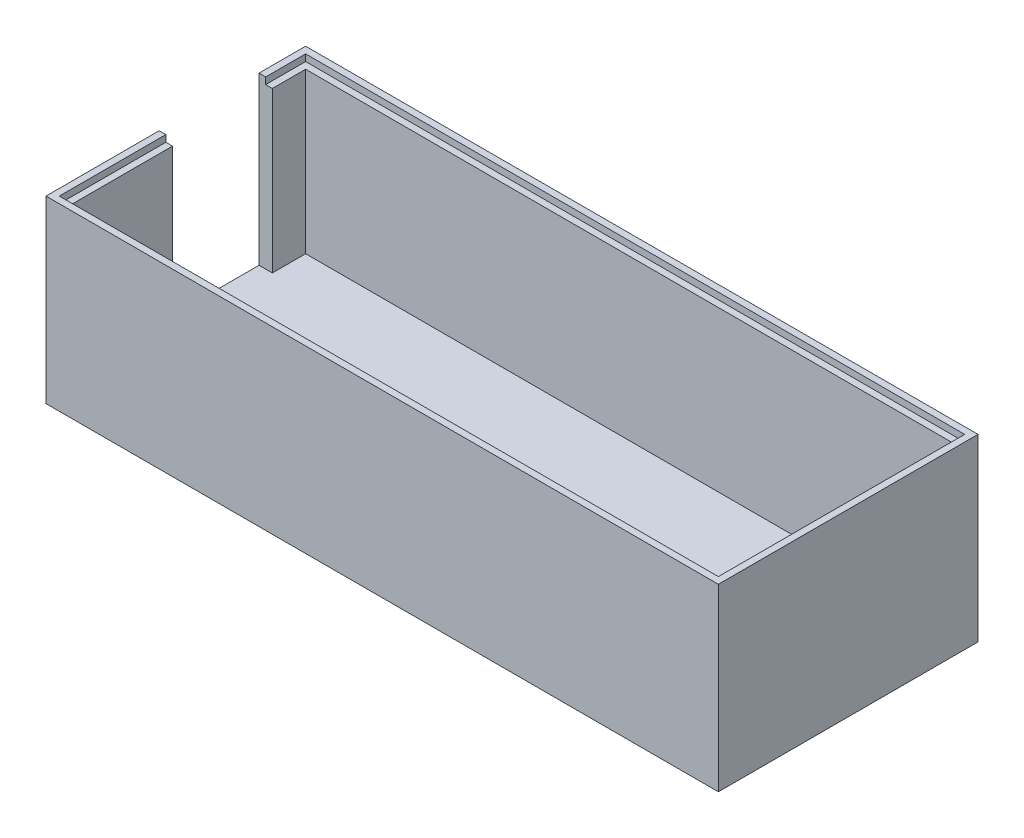
SolidWorks part; units mm, degrees
ref_plane "Front Plane" through (0, 0, 0) normal (0, 0, 1) x (1, 0, 0)
ref_plane "Top Plane" through (0, 0, 0) normal (0, 1, 0) x (1, 0, 0)
ref_plane "Right Plane" through (0, 0, 0) normal (1, 0, 0) x (0, 0, -1)
sketch "Sketch1" plane through (0, 0, 0) normal (0, 1, 0) x (1, 0, 0)
  line L0 (0, 39) -> (0, 32)
  line L1 (0, 0) -> (101, 0)
  line L3 (0, 39) -> (101, 39)
  line L4 (101, 0) -> (101, 39)
  line L5 (0, 32) -> (2, 32)
  line L6 (2, 32) -> (2, 37)
  line L7 (2, 37) -> (99, 37)
  line L8 (99, 37) -> (99, 2)
  line L9 (99, 2) -> (2, 2)
  line L10 (2, 2) -> (2, 17)
  line L11 (2, 17) -> (0, 17)
  line L12 (0, 17) -> (0, 0)
extrude "Boss-Extrude1" add sketch "Sketch1" along normal blind 25
sketch "Sketch2" plane through (0, 0, 0) normal (0, -1, 0) x (-1, 0, 0)
  line L1 (0, 0) -> (-101, 0)
  line L2 (0, 0) -> (0, 39)
  line L3 (0, 39) -> (-101, 39)
  line L4 (-101, 0) -> (-101, 39)
extrude "Boss-Extrude2" add sketch "Sketch2" along normal blind 2
sketch "Sketch3" plane through (0, 25, 0) normal (0, 1, 0) x (1, 0, 0)
  line L0 (2, 32) -> (1, 32)
  line L1 (0, 32) -> (2, 32) construction
  line L2 (1, 32) -> (1, 38)
  line L3 (1, 38) -> (100, 38)
  line L4 (100, 38) -> (100, 1)
  line L5 (100, 1) -> (1, 1)
  line L6 (1, 1) -> (1, 17)
  line L7 (2, 17) -> (0, 17) construction
  line L8 (1, 17) -> (2, 17)
  line L9 (2, 17) -> (2, 2)
  line L10 (2, 2) -> (99, 2)
  line L11 (99, 2) -> (99, 37)
  line L12 (99, 37) -> (2, 37)
  line L13 (2, 37) -> (2, 32)
extrude "Cut-Extrude1" cut sketch "Sketch3" against normal blind 1
